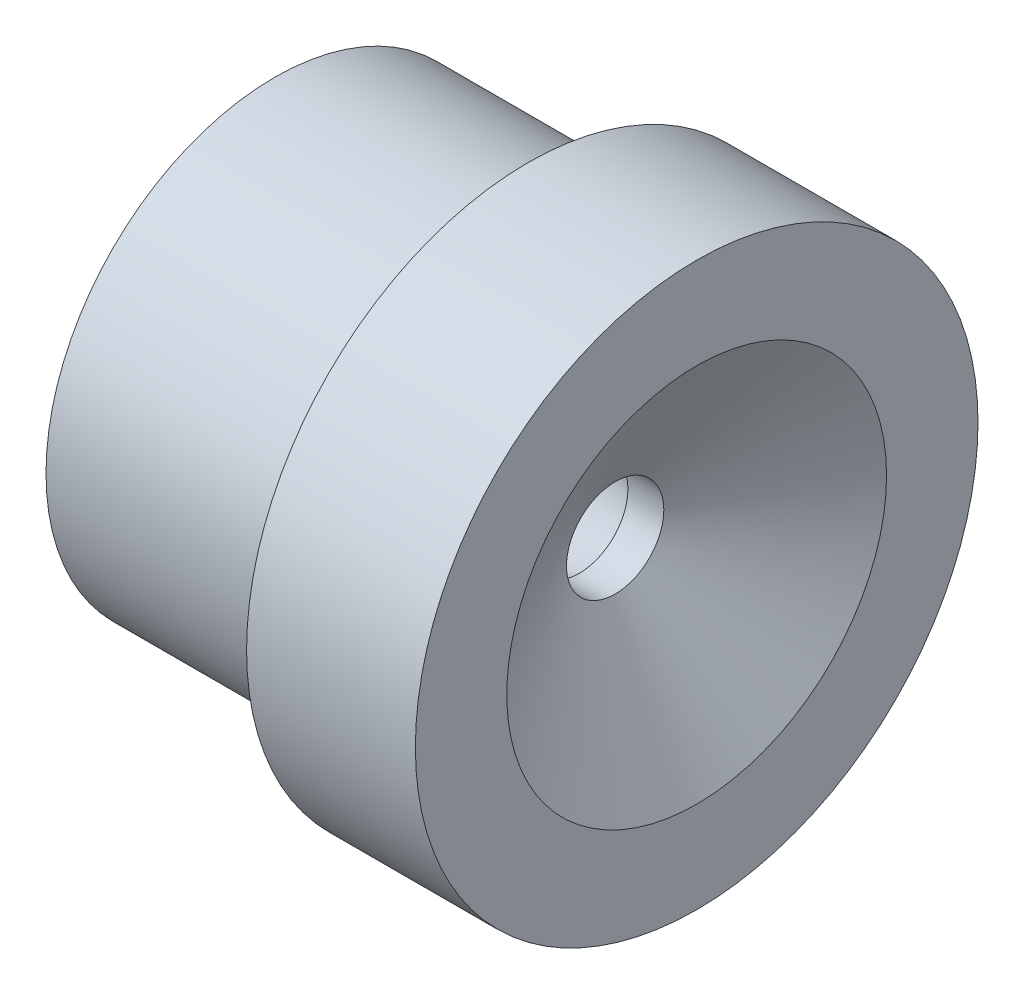
SolidWorks part; units mm, degrees
material "C (Graphite)"
ref_plane "Front Plane" through (0, 0, 0) normal (0, 0, 1) x (1, 0, 0)
ref_plane "Top Plane" through (0, 0, 0) normal (0, 1, 0) x (1, 0, 0)
ref_plane "Right Plane" through (0, 0, 0) normal (1, 0, 0) x (0, 0, -1)
sketch "Sketch1" plane through (0, 0, 0) normal (0, 1, 0) x (1, 0, 0)
  line L0 (0, 0) -> (0, 4.1275)
  line L1 (0, 4.1275) -> (-3.6808, 10.5029)
  line L2 (-3.6808, 10.5029) -> (-5.3014, 10.5029)
  line L3 (-5.3014, 10.5029) -> (-19.05, 6.819)
  line L4 (-19.05, 6.819) -> (-19.05, 2.3749)
  line L5 (-19.05, 2.3749) -> (-7.62, 2.3749)
  line L6 (-7.62, 2.3749) -> (-7.62, 0)
  line L9 (-7.62, 0) -> (0, 0)
  line L10 (5.1187, 12.7) -> (-11.0703, 12.7) construction
  dimension "D1" = 25.4
  dimension "D2" = 4.3942
  dimension "D3" = 60
  dimension "D4" = 15
  dimension "D5" = 17.145
  dimension "D6" = 1.6205
  dimension "D7" = 7.62
  dimension "D8" = 19.05
  dimension "D9" = 20.6502
revolve "Revolve1" add sketch "Sketch1" angle 360 about L10
